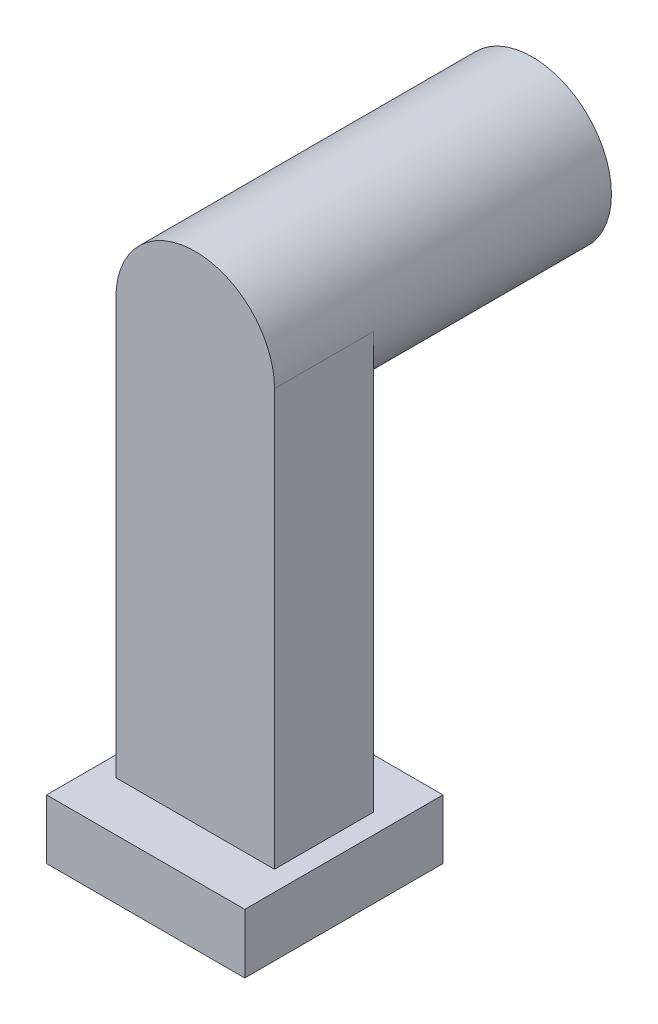
SolidWorks part; units mm, degrees
ref_plane "Front Plane" through (0, 0, 0) normal (0, 0, 1) x (1, 0, 0)
ref_plane "Top Plane" through (0, 0, 0) normal (0, 1, 0) x (1, 0, 0)
ref_plane "Right Plane" through (0, 0, 0) normal (1, 0, 0) x (0, 0, -1)
sketch "Sketch1" plane through (0, 0, 0) normal (0, 0, 1) x (1, 0, 0)
  circle A1 centre (0, 0) radius 1.9
  dimension "D2" = 3.8
extrude "Boss-Extrude1" add sketch "Sketch1" along normal blind 0.0001 from offset 13
sketch "Sketch2" plane through (0, 0, 0) normal (0, 0, 1) x (1, 0, 0)
  circle A0 centre (0, 0) radius 4
  dimension "D1" = 8
extrude "Boss-Extrude2" add sketch "Sketch2" along normal blind 17 from offset 13
sketch "Sketch6" plane through (0, 0, 0) normal (0, 1, 0) x (1, 0, 0)
  line L0 (0, -30) -> (0, -25) construction
  line L1 (-4, -30) -> (4, -30) construction
  line L2 (-4, -13) -> (-4, -30) construction
  line L3 (-4, -25) -> (4, -25)
  line L4 (-4, -25) -> (-4, -30)
  line L5 (-4, -30) -> (4, -30)
  line L6 (4, -25) -> (4, -30)
  dimension "D1" = 5
extrude "Boss-Extrude3" add sketch "Sketch6" against normal blind 21
sketch "Sketch7" plane through (0, -21, 0) normal (0, -1, 0) x (1, 0, 0)
  line L0 (0, 30) -> (0, 25) construction
  line L1 (-4, 30) -> (4, 30) construction
  line L2 (-4, 25) -> (4, 25) construction
  line L3 (-4, 27.5) -> (4, 27.5) construction
  line L4 (-4, 25) -> (-4, 30) construction
  line L5 (4, 30) -> (4, 25) construction
  line L6 (5, 32.5) -> (-5, 32.5)
  line L7 (-5, 32.5) -> (-5, 22.5)
  line L10 (5, 22.5) -> (-5, 22.5)
  line L11 (5, 32.5) -> (5, 22.5)
  point P17 (-5, 27.5)
  point P18 (0, 32.5)
  point P19 (0, 22.5)
  dimension "D1" = 5
  dimension "D2" = 5
extrude "Boss-Extrude4" add sketch "Sketch7" along normal blind 3
